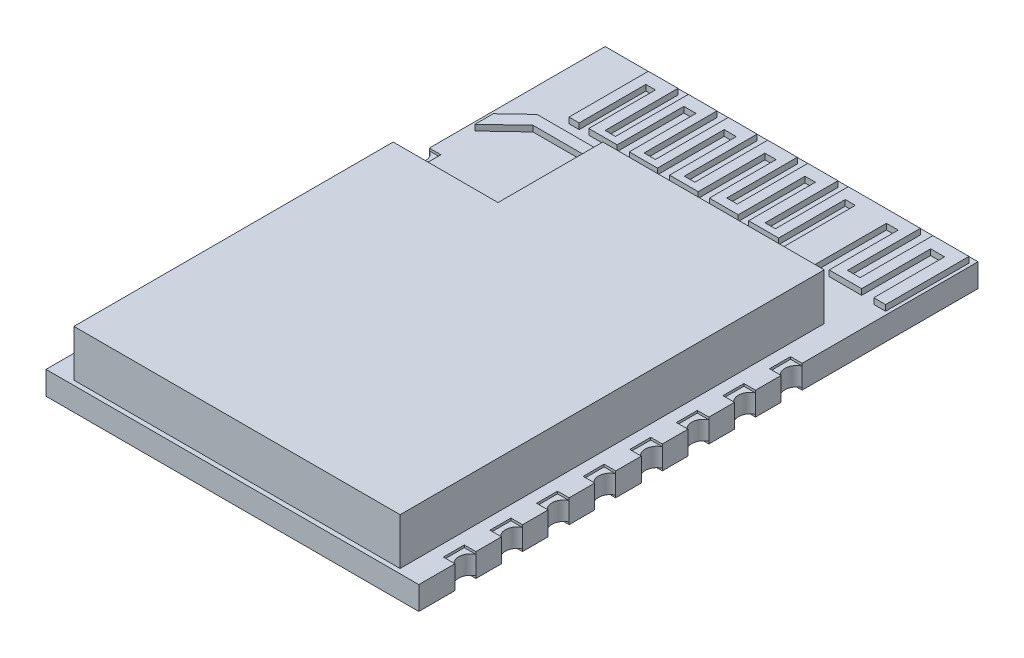
SolidWorks part; units mm, degrees
ref_plane "前基準面" through (0, 0, 0) normal (0, 0, 1) x (1, 0, 0)
ref_plane "上基準面" through (0, 0, 0) normal (0, 1, 0) x (1, 0, 0)
ref_plane "右基準面" through (0, 0, 0) normal (1, 0, 0) x (0, 0, -1)
sketch "草圖1" plane through (0, 0, 0) normal (0, 1, 0) x (1, 0, 0)
  line L5 (-8, 12) -> (8, 12)
  line L6 (-8, 12) -> (-8, -12)
  line L7 (-8, -12) -> (8, -12)
  line L8 (8, 12) -> (8, -12)
  line L9 (-8, 12) -> (8, -12) construction
  line L10 (-8, -12) -> (8, 12) construction
  point P0 (0, 0)
  dimension "D1" = 16
  dimension "24" = 24
extrude "填料-伸長1" add sketch "草圖1" along normal blind 1
sketch "草圖2" plane through (0, 1, 0) normal (0, 1, 0) x (1, 0, 0)
  line L0 (0, 0) -> (0, -5.3119)
  line L1 (-8.003, -9.55) -> (-7.503, -9.55)
  line L2 (-8.003, -9.55) -> (-8.003, -10.45)
  line L3 (-8.003, -10.45) -> (-7.503, -10.45)
  line L4 (-7.503, -9.55) -> (-7.503, -10.45)
  line L5 (8.003, -10.45) -> (7.503, -10.45)
  line L6 (7.503, -9.55) -> (7.503, -10.45)
  line L7 (8.003, -9.55) -> (7.503, -9.55)
  line L8 (8.003, -9.55) -> (8.003, -10.45)
  line L9 (-8.003, -7.55) -> (-8.003, -8.45)
  line L10 (-8.003, -7.55) -> (-7.503, -7.55)
  line L11 (-7.503, -7.55) -> (-7.503, -8.45)
  line L12 (-8.003, -8.45) -> (-7.503, -8.45)
  line L13 (-8.003, -5.55) -> (-8.003, -6.45)
  line L14 (-8.003, -5.55) -> (-7.503, -5.55)
  line L15 (-7.503, -5.55) -> (-7.503, -6.45)
  line L16 (-8.003, -6.45) -> (-7.503, -6.45)
  line L17 (-8.003, -3.55) -> (-8.003, -4.45)
  line L18 (-8.003, -3.55) -> (-7.503, -3.55)
  line L19 (-7.503, -3.55) -> (-7.503, -4.45)
  line L20 (-8.003, -4.45) -> (-7.503, -4.45)
  line L21 (-8.003, -1.55) -> (-8.003, -2.45)
  line L22 (-8.003, -1.55) -> (-7.503, -1.55)
  line L23 (-7.503, -1.55) -> (-7.503, -2.45)
  line L24 (-8.003, -2.45) -> (-7.503, -2.45)
  line L25 (-8.003, 0.45) -> (-8.003, -0.45)
  line L26 (-8.003, 0.45) -> (-7.503, 0.45)
  line L27 (-7.503, 0.45) -> (-7.503, -0.45)
  line L28 (-8.003, -0.45) -> (-7.503, -0.45)
  line L29 (-8.003, 2.45) -> (-8.003, 1.55)
  line L30 (-8.003, 2.45) -> (-7.503, 2.45)
  line L31 (-7.503, 2.45) -> (-7.503, 1.55)
  line L32 (-8.003, 1.55) -> (-7.503, 1.55)
  line L33 (-8.003, 4.45) -> (-8.003, 3.55)
  line L34 (-8.003, 4.45) -> (-7.503, 4.45)
  line L35 (-7.503, 4.45) -> (-7.503, 3.55)
  line L36 (-8.003, 3.55) -> (-7.503, 3.55)
  line L42 (8.003, -8.45) -> (7.503, -8.45)
  line L43 (7.503, -7.55) -> (7.503, -8.45)
  line L44 (8.003, -7.55) -> (7.503, -7.55)
  line L45 (8.003, -7.55) -> (8.003, -8.45)
  line L46 (8.003, -6.45) -> (7.503, -6.45)
  line L47 (7.503, -5.55) -> (7.503, -6.45)
  line L48 (8.003, -5.55) -> (7.503, -5.55)
  line L49 (8.003, -5.55) -> (8.003, -6.45)
  line L50 (8.003, -4.45) -> (7.503, -4.45)
  line L51 (7.503, -3.55) -> (7.503, -4.45)
  line L52 (8.003, -3.55) -> (7.503, -3.55)
  line L53 (8.003, -3.55) -> (8.003, -4.45)
  line L54 (8.003, -2.45) -> (7.503, -2.45)
  line L55 (7.503, -1.55) -> (7.503, -2.45)
  line L56 (8.003, -1.55) -> (7.503, -1.55)
  line L57 (8.003, -1.55) -> (8.003, -2.45)
  line L58 (8.003, -0.45) -> (7.503, -0.45)
  line L59 (7.503, 0.45) -> (7.503, -0.45)
  line L60 (8.003, 0.45) -> (7.503, 0.45)
  line L61 (8.003, 0.45) -> (8.003, -0.45)
  line L62 (8.003, 1.55) -> (7.503, 1.55)
  line L63 (7.503, 2.45) -> (7.503, 1.55)
  line L64 (8.003, 2.45) -> (7.503, 2.45)
  line L65 (8.003, 2.45) -> (8.003, 1.55)
  line L66 (8.003, 3.55) -> (7.503, 3.55)
  line L67 (7.503, 4.45) -> (7.503, 3.55)
  line L68 (8.003, 4.45) -> (7.503, 4.45)
  line L69 (8.003, 4.45) -> (8.003, 3.55)
  point P4 (-8.003, -10)
  line M6 (8, -12) -> (8, 12)
  line M8 (-8, 12) -> (-8, -12)
  dimension "D1" = 2
  dimension "D2" = 8
  dimension "D3" = 8
extrude "除料-伸長1" cut sketch "草圖2" against normal blind 0.1 contours L32 L31 L30 M8 | L28 L27 L26 M8 | L24 L23 L22 M8 | L20 L19 L18 M8 | L16 L15 L14 M8 | L12 L11 L10 M8 | L4 L1 L3 M8 | L7 L6 L5 M6 | L44 L43 L42 M6 | L48 L47 L46 M6 | L52 L51 L50 M6 | L56 L55 L54 M6 | L60 L59 L58 M6 | L68 L67 L66 M6 | L64 L63 L62 M6 | L35 L36 L33 L34
sketch "草圖3" plane through (0, 0, 0) normal (0, -1, 0) x (1, 0, 0)
  line L0 (7, 7.55) -> (7, 8.45)
  line L1 (8, 12) -> (8, -12) construction
  line L6 (7, 9.55) -> (8, 9.55)
  line L7 (7, 9.55) -> (7, 10.45)
  line L8 (7, 10.45) -> (8, 10.45)
  line L9 (8, 9.55) -> (8, 10.45)
  line L10 (-8, 12) -> (8, 12) construction
  line L11 (7, 7.55) -> (8, 7.55)
  line L12 (8, 7.55) -> (8, 8.45)
  line L13 (7, 8.45) -> (8, 8.45)
  line L14 (7, 5.55) -> (7, 6.45)
  line L15 (7, 5.55) -> (8, 5.55)
  line L16 (8, 5.55) -> (8, 6.45)
  line L17 (7, 6.45) -> (8, 6.45)
  line L18 (7, 3.55) -> (7, 4.45)
  line L19 (7, 3.55) -> (8, 3.55)
  line L20 (8, 3.55) -> (8, 4.45)
  line L21 (7, 4.45) -> (8, 4.45)
  line L22 (7, 1.55) -> (7, 2.45)
  line L23 (7, 1.55) -> (8, 1.55)
  line L24 (8, 1.55) -> (8, 2.45)
  line L25 (7, 2.45) -> (8, 2.45)
  line L26 (7, -0.45) -> (7, 0.45)
  line L27 (7, -0.45) -> (8, -0.45)
  line L28 (8, -0.45) -> (8, 0.45)
  line L29 (7, 0.45) -> (8, 0.45)
  line L30 (7, -2.45) -> (7, -1.55)
  line L31 (7, -2.45) -> (8, -2.45)
  line L32 (8, -2.45) -> (8, -1.55)
  line L33 (7, -1.55) -> (8, -1.55)
  line L34 (7, -4.45) -> (7, -3.55)
  line L35 (7, -4.45) -> (8, -4.45)
  line L36 (8, -4.45) -> (8, -3.55)
  line L37 (7, -3.55) -> (8, -3.55)
  line L38 (0, 0) -> (0, -2.1829)
  line L39 (-7, 10.45) -> (-8, 10.45)
  line L40 (-8, 9.55) -> (-8, 10.45)
  line L41 (-7, 9.55) -> (-8, 9.55)
  line L42 (-7, 9.55) -> (-7, 10.45)
  line L43 (-7, -4.45) -> (-8, -4.45)
  line L44 (-8, -4.45) -> (-8, -3.55)
  line L45 (-7, -3.55) -> (-8, -3.55)
  line L46 (-7, -4.45) -> (-7, -3.55)
  line L47 (-7, -2.45) -> (-8, -2.45)
  line L48 (-8, -2.45) -> (-8, -1.55)
  line L49 (-7, -1.55) -> (-8, -1.55)
  line L50 (-7, -2.45) -> (-7, -1.55)
  line L51 (-7, -0.45) -> (-8, -0.45)
  line L52 (-8, -0.45) -> (-8, 0.45)
  line L53 (-7, 0.45) -> (-8, 0.45)
  line L54 (-7, -0.45) -> (-7, 0.45)
  line L55 (-7, 1.55) -> (-8, 1.55)
  line L56 (-8, 1.55) -> (-8, 2.45)
  line L57 (-7, 2.45) -> (-8, 2.45)
  line L58 (-7, 1.55) -> (-7, 2.45)
  line L59 (-7, 3.55) -> (-8, 3.55)
  line L60 (-8, 3.55) -> (-8, 4.45)
  line L61 (-7, 4.45) -> (-8, 4.45)
  line L62 (-7, 3.55) -> (-7, 4.45)
  line L63 (-7, 5.55) -> (-8, 5.55)
  line L64 (-8, 5.55) -> (-8, 6.45)
  line L65 (-7, 6.45) -> (-8, 6.45)
  line L66 (-7, 5.55) -> (-7, 6.45)
  line L67 (-7, 7.55) -> (-8, 7.55)
  line L68 (-8, 7.55) -> (-8, 8.45)
  line L69 (-7, 8.45) -> (-8, 8.45)
  line L70 (-7, 7.55) -> (-7, 8.45)
  point P8 (8, 10)
  dimension "D1" = 2
  dimension "D2" = 0.9
  dimension "D3" = 8
extrude "除料-伸長2" cut sketch "草圖3" against normal blind 0.1 contours L67 L70 L69 L9 | L63 L66 L65 L9 | L59 L62 L61 L9 | L51 L54 L53 L9 | L47 L50 L49 L9 | L43 L46 L45 L9 | L33 L30 L31 L7 | L29 L26 L27 L7 | L25 L22 L23 L7 | L21 L18 L19 L7 | L13 L0 L11 L7 | L8 L7 L6 | L41 L40 L39 L42 | L58 L57 L56 L55 | L36 L37 L34 L35 | L17 L16 L15 L14
sketch "草圖8" plane through (0, 1, 0) normal (0, 1, 0) x (1, 0, 0)
  line L0 (-8, -12) -> (8, -12) construction
  line L1 (-1, 0.6) -> (3.7, 0.6)
  line L2 (-1, 0.6) -> (-1, -4.1)
  line L3 (-1, -4.1) -> (3.7, -4.1)
  line L4 (3.7, 0.6) -> (3.7, -4.1)
  line L5 (-1, 0.6) -> (3.7, -4.1) construction
  line L6 (-1, -4.1) -> (3.7, 0.6) construction
  line L7 (-8, -2.45) -> (-8, -3.55) construction
  point P0 (1.35, -1.75)
  dimension "D1" = 7.9
  dimension "D2" = 7
  dimension "D3" = 4.7
  dimension "D4" = 4.7
extrude "除料-伸長3" cut sketch "草圖8" against normal blind 0.1
sketch "草圖12" plane through (0, 0.9, 0) normal (0, 1, 0) x (1, 0, 0)
  line L0 (-1, 0.6) -> (-1, -4.1) construction
  line L1 (-1, -4.1) -> (3.7, -4.1) construction
  circle A1 centre (-0.51, -3.65) radius 0.2
  circle A2 centre (0.42, -3.65) radius 0.2
  circle A3 centre (1.35, -3.65) radius 0.2
  circle A4 centre (2.28, -3.65) radius 0.2
  circle A5 centre (3.21, -3.65) radius 0.2
  circle A6 centre (-0.51, -2.72) radius 0.2
  circle A7 centre (0.42, -2.72) radius 0.2
  circle A8 centre (1.35, -2.72) radius 0.2
  circle A9 centre (2.28, -2.72) radius 0.2
  circle A10 centre (3.21, -2.72) radius 0.2
  circle A11 centre (-0.51, -1.79) radius 0.2
  circle A12 centre (0.42, -1.79) radius 0.2
  circle A13 centre (1.35, -1.79) radius 0.2
  circle A14 centre (2.28, -1.79) radius 0.2
  circle A15 centre (3.21, -1.79) radius 0.2
  circle A16 centre (-0.51, -0.86) radius 0.2
  circle A17 centre (0.42, -0.86) radius 0.2
  circle A18 centre (1.35, -0.86) radius 0.2
  circle A19 centre (2.28, -0.86) radius 0.2
  circle A20 centre (3.21, -0.86) radius 0.2
  circle A21 centre (-0.51, 0.07) radius 0.2
  circle A22 centre (0.42, 0.07) radius 0.2
  circle A23 centre (1.35, 0.07) radius 0.2
  circle A24 centre (2.28, 0.07) radius 0.2
  circle A25 centre (3.21, 0.07) radius 0.2
  dimension "D1" = 0.49
  dimension "D2" = 0.45
  dimension "D3" = 5
  dimension "D4" = 5
extrude "除料-伸長4" cut sketch "草圖12" against normal blind 0.1
sketch "草圖13" plane through (0, 1, 0) normal (0, 1, 0) x (1, 0, 0)
  line L5 (-1, 0.6) -> (3.7, 0.6)
  line L6 (-1, 0.6) -> (-1, -4.1)
  line L7 (-1, -4.1) -> (3.7, -4.1)
  line L8 (3.7, 0.6) -> (3.7, -4.1)
extrude "填料-伸長2" add sketch "草圖13" against normal blind 0.5
sketch "草圖15" plane through (0, 0, 0) normal (0, -1, 0) x (1, 0, 0)
  line L0 (-8, 12) -> (8, 12) construction
  line L1 (1, -0.6) -> (-3.7, -0.6)
  line L2 (1, -0.6) -> (1, 4.1)
  line L3 (1, 4.1) -> (-3.7, 4.1)
  line L4 (-3.7, -0.6) -> (-3.7, 4.1)
  line L5 (1, -0.6) -> (-3.7, 4.1) construction
  line L6 (1, 4.1) -> (-3.7, -0.6) construction
  line L7 (8, 1.55) -> (8, 0.45) construction
  point P0 (-1.35, 1.75)
  point P9 (8, 1)
  dimension "D1" = 7.9
  dimension "D2" = 7
  dimension "D3" = 4.7
  dimension "D4" = 4.7
extrude "除料-伸長5" cut sketch "草圖15" against normal blind 0.1
sketch "草圖16" plane through (0, 0, 0) normal (0, -1, 0) x (1, 0, 0)
  line L0 (1, 4.1) -> (-3.7, 4.1) construction
  line L1 (1, -0.6) -> (1, 4.1) construction
  circle A0 centre (0.51, 3.61) radius 0.2
  circle A1 centre (-0.42, 3.61) radius 0.2
  circle A2 centre (-1.35, 3.61) radius 0.2
  circle A3 centre (-2.28, 3.61) radius 0.2
  circle A4 centre (-3.21, 3.61) radius 0.2
  circle A5 centre (-3.21, 2.68) radius 0.2
  circle A6 centre (-2.28, 2.68) radius 0.2
  circle A7 centre (-1.35, 2.68) radius 0.2
  circle A8 centre (-0.42, 2.68) radius 0.2
  circle A9 centre (0.51, 2.68) radius 0.2
  circle A10 centre (-3.21, 1.75) radius 0.2
  circle A11 centre (-2.28, 1.75) radius 0.2
  circle A12 centre (-1.35, 1.75) radius 0.2
  circle A13 centre (-0.42, 1.75) radius 0.2
  circle A14 centre (0.51, 1.75) radius 0.2
  circle A15 centre (-3.21, 0.82) radius 0.2
  circle A16 centre (-2.28, 0.82) radius 0.2
  circle A17 centre (-1.35, 0.82) radius 0.2
  circle A18 centre (-0.42, 0.82) radius 0.2
  circle A19 centre (0.51, 0.82) radius 0.2
  circle A20 centre (-3.21, -0.11) radius 0.2
  circle A21 centre (-2.28, -0.11) radius 0.2
  circle A22 centre (-1.35, -0.11) radius 0.2
  circle A23 centre (-0.42, -0.11) radius 0.2
  circle A24 centre (0.51, -0.11) radius 0.2
  dimension "D1" = 0.49
  dimension "D2" = 0.49
  dimension "D3" = 5
  dimension "D4" = 5
extrude "除料-伸長6" cut sketch "草圖16" against normal blind 0.25
sketch "草圖17" plane through (0, 1, 0) normal (0, 1, 0) x (1, 0, 0)
  line L0 (-8, -12) -> (8, -12) construction
  line L5 (-2.5, 6.4) -> (7, 6.4)
  line L6 (-7, 1.4) -> (-7, -10.8)
  line L7 (-7, -10.8) -> (7, -10.8)
  line L8 (7, 6.4) -> (7, -10.8)
  line L9 (-8, 12) -> (-8, 4.45) construction
  line L10 (8, 4.45) -> (8, 12) construction
  line L16 (-2.5, 6.4) -> (-2.5, 1.9)
  line L17 (-2.5, 1.9) -> (-7, 1.9)
  line L18 (-7, 1.9) -> (-7, 1.4)
  dimension "D1" = 1.2
  dimension "D2" = 1
  dimension "D3" = 1
extrude "填料-伸長4" add sketch "草圖17" along normal blind 2
sketch "草圖18" plane through (0, 1, 0) normal (0, 1, 0) x (1, 0, 0)
  line L1 (-8, 4.45) -> (-8, 3.55)
  line L3 (-8, 2.45) -> (-8, 1.55)
  line L4 (-8, 0.45) -> (-8, -0.45)
  line L5 (-8, -1.55) -> (-8, -2.45)
  line L6 (-8, -3.55) -> (-8, -4.45)
  line L7 (-8, -5.55) -> (-8, -6.45)
  line L8 (-8, -7.55) -> (-8, -8.45)
  line L9 (-8, -9.55) -> (-8, -10.45)
  line L12 (8, 4.45) -> (8, 3.55)
  line L13 (8, 2.45) -> (8, 1.55)
  line L14 (8, 0.45) -> (8, -0.45)
  line L15 (8, -1.55) -> (8, -2.45)
  line L16 (8, -3.55) -> (8, -4.45)
  line L17 (8, -5.55) -> (8, -6.45)
  line L18 (8, -7.55) -> (8, -8.45)
  line L19 (8, -9.55) -> (8, -10.45)
  arc A0 (-8, 4.45) -> (-8, 3.55) centre (-8.2179, 4) cw
  arc A1 (-8, 2.45) -> (-8, 1.55) centre (-8.2179, 2) cw
  arc A2 (-8, 0.45) -> (-8, -0.45) centre (-8.2179, 0) cw
  arc A3 (-8, -1.55) -> (-8, -2.45) centre (-8.2179, -2) cw
  arc A4 (-8, -3.55) -> (-8, -4.45) centre (-8.2179, -4) cw
  arc A5 (-8, -5.55) -> (-8, -6.45) centre (-8.2179, -6) cw
  arc A6 (-8, -7.55) -> (-8, -8.45) centre (-8.2179, -8) cw
  arc A7 (-8, -9.55) -> (-8, -10.45) centre (-8.2179, -10) cw
  arc A8 (8, 4.45) -> (8, 3.55) centre (8.2179, 4) ccw
  arc A9 (8, 2.45) -> (8, 1.55) centre (8.2179, 2) ccw
  arc A10 (8, 0.45) -> (8, -0.45) centre (8.2179, 0) ccw
  arc A11 (8, -1.55) -> (8, -2.45) centre (8.2179, -2) ccw
  arc A12 (8, -3.55) -> (8, -4.45) centre (8.2179, -4) ccw
  arc A13 (8, -5.55) -> (8, -6.45) centre (8.2179, -6) ccw
  arc A14 (8, -7.55) -> (8, -8.45) centre (8.2179, -8) ccw
  arc A15 (8, -9.55) -> (8, -10.45) centre (8.2179, -10) ccw
  dimension "D1" = 8
extrude "除料-伸長7" cut sketch "草圖18" against normal blind 2
sketch "草圖19" plane through (0, 1, 0) normal (0, 1, 0) x (1, 0, 0)
  line L0 (-144.5969, 121.1687) -> (-19.9302, 121.1687) construction
  line L1 (-7, -10.8) -> (-7, -11.8025)
  line L2 (-7, -11.8025) -> (7, -11.8025)
  line L3 (7, -10.8) -> (7, -11.8025)
  line L4 (7, -10.8) -> (7, -11.8025)
  line L5 (-7, -10.8) -> (7, -10.8)
extrude "填料-伸長5" add sketch "草圖19" along normal up to surface (2 mm away) contours L5 L1 L2 L3 up to face at (-0.8333, 3, 0.8333)
sketch "草圖20" plane through (0, 1, 0) normal (0, 1, 0) x (1, 0, 0)
  line L0 (23.4441, 125.3473) -> (148.1108, 125.3473) construction
  line L1 (2.7746, 7.2994) -> (2.7746, 6.4)
  line L3 (7, 6.4) -> (-2.5, 6.4) construction
  line L4 (2.7746, 7.2994) -> (4.8557, 7.2994)
  line L5 (4.8557, 7.2994) -> (4.8557, 11.2142)
  line L6 (4.8557, 11.2142) -> (5.3615, 11.2142)
  line L7 (5.3615, 11.2142) -> (5.3615, 8.253)
  line L8 (5.3615, 8.253) -> (6.7537, 8.253)
  line L9 (6.7537, 8.253) -> (6.7537, 11.2142)
  line L10 (6.7537, 11.2142) -> (7.3504, 11.2142)
  line L11 (7.3504, 11.2142) -> (7.3504, 8.1756)
  line L12 (7.3504, 8.1756) -> (7.8586, 8.1756)
  line L13 (7.8586, 8.1756) -> (7.8586, 11.7556)
  line L14 (7.8586, 11.7556) -> (6.3117, 11.7556)
  line L15 (6.3117, 11.7556) -> (6.3117, 8.6286)
  line L16 (6.3117, 8.6286) -> (5.8587, 8.6286)
  line L17 (5.8587, 8.6286) -> (5.7703, 8.6286)
  line L18 (5.7703, 8.6286) -> (5.7703, 11.7556)
  line L19 (5.7703, 11.7556) -> (2.6765, 11.7556)
  line L20 (2.6765, 11.7556) -> (2.6765, 8.6286)
  line L21 (2.6765, 8.6286) -> (2.2345, 8.6286)
  line L22 (2.2345, 8.6286) -> (2.2345, 11.7556)
  line L23 (2.2345, 11.7556) -> (0.9417, 11.7556)
  line L24 (0.9417, 11.7556) -> (0.9417, 8.7281)
  line L25 (0.9417, 8.7281) -> (0.4887, 8.7281)
  line L26 (0.4887, 8.7281) -> (0.4887, 11.7556)
  line L27 (0.4887, 11.7556) -> (-0.782, 11.7556)
  line L28 (-0.782, 11.7556) -> (-0.782, 8.6286)
  line L29 (-0.782, 8.6286) -> (-1.235, 8.6286)
  line L30 (-1.235, 8.6286) -> (-1.235, 11.7556)
  line L31 (-1.235, 11.7556) -> (-2.4725, 11.7556)
  line L32 (-2.4725, 11.7556) -> (-2.4725, 8.6286)
  line L33 (-2.4725, 8.6286) -> (-2.9587, 8.6286)
  line L34 (-2.9587, 8.6286) -> (-2.9587, 11.7556)
  line L35 (-2.9587, 11.7556) -> (-4.1852, 11.7556)
  line L36 (-4.1852, 11.7556) -> (-4.1852, 8.6286)
  line L37 (-4.1852, 8.6286) -> (-4.6323, 8.6286)
  line L38 (-4.6323, 8.6286) -> (-4.6323, 11.7556)
  line L39 (-4.6323, 11.7556) -> (-5.9045, 11.7556)
  line L40 (-5.9045, 11.7556) -> (-5.9045, 8.3512)
  line L41 (-5.9045, 8.3512) -> (-5.4695, 8.3512)
  line L42 (-5.4695, 8.3512) -> (-5.4695, 11.2142)
  line L43 (-5.4695, 11.2142) -> (-5.0563, 11.2142)
  line L44 (-5.0563, 11.2142) -> (-5.0563, 8.3512)
  line L45 (-5.0563, 8.3512) -> (-3.8385, 8.3512)
  line L46 (-3.8385, 8.3512) -> (-3.8385, 11.2142)
  line L47 (-3.8385, 11.2142) -> (-3.3166, 11.2142)
  line L48 (-3.3166, 11.2142) -> (-3.3166, 8.3512)
  line L49 (-3.3166, 8.3512) -> (-2.1096, 8.3512)
  line L50 (-2.1096, 8.3512) -> (-2.1096, 11.2142)
  line L51 (-2.1096, 11.2142) -> (-1.5877, 11.2142)
  line L52 (-1.5877, 11.2142) -> (-1.5877, 8.3512)
  line L53 (-1.5877, 8.3512) -> (-0.3589, 8.3512)
  line L54 (-0.3589, 8.3512) -> (-0.3589, 11.2142)
  line L55 (-0.3589, 11.2142) -> (0.1195, 11.2142)
  line L56 (0.1195, 11.2142) -> (0.1195, 8.3512)
  line L57 (0.1195, 8.3512) -> (1.3591, 8.3512)
  line L58 (1.3591, 8.3512) -> (1.3591, 11.2142)
  line L59 (1.3591, 11.2142) -> (1.8049, 11.2142)
  line L60 (1.8049, 11.2142) -> (1.8049, 8.3512)
  line L61 (1.8049, 8.3512) -> (3.088, 8.3512)
  line L62 (3.088, 8.3512) -> (3.088, 11.2142)
  line L63 (3.088, 11.2142) -> (3.523, 11.2142)
  line L64 (3.523, 11.2142) -> (3.523, 7.764)
  line L65 (3.523, 7.764) -> (-6.6874, 7.764)
  line L66 (-6.6874, 7.764) -> (-7.6552, 6.8497)
  line L67 (-7.6552, 6.8497) -> (-7.6552, 6.1428)
  line L68 (-6.3743, 7.2733) -> (2.2333, 7.2733)
  line L69 (2.2333, 7.2733) -> (2.25, 6.4)
  line L70 (-6.3743, 7.2733) -> (-7.5709, 6.1428)
  line L71 (7, 6.4) -> (-2.5, 6.4) construction
  line L72 (2.25, 6.4) -> (2.7746, 6.4)
  line L73 (-7.6552, 6.1428) -> (-7.6552, 6.0749)
  line L75 (-7.5709, 6.1428) -> (-7.6552, 6.0632)
  line L76 (-7.6552, 6.0632) -> (-7.6552, 6.0749)
ref_plane "平面1" through (8, 1, -4.45) normal (0, 0, -1) x (-1, 0, 0)
extrude "填料-伸長7" add sketch "草圖20" along normal blind 0.25 contours L65 L66 L67 L73 L76 L75 L70 L68 L69 L72 L1 L4 L5 L6 L7 L8 L9 L10 L11 L12 L13 L14 L15 L16 L17 L18 L19 L20 L21 L22 L23 L24 L25 L26 L27 L28 L29 L30 L31 L32 L33 L34 L35 L36 L37 L38 L39 L40 L41 L42 L43 L44 L45 L46 L47 L48 L49 L50 L51 L52 L53 L54 L55 L56 L57 L58 L59 L60 L61 L62 L63 L64
